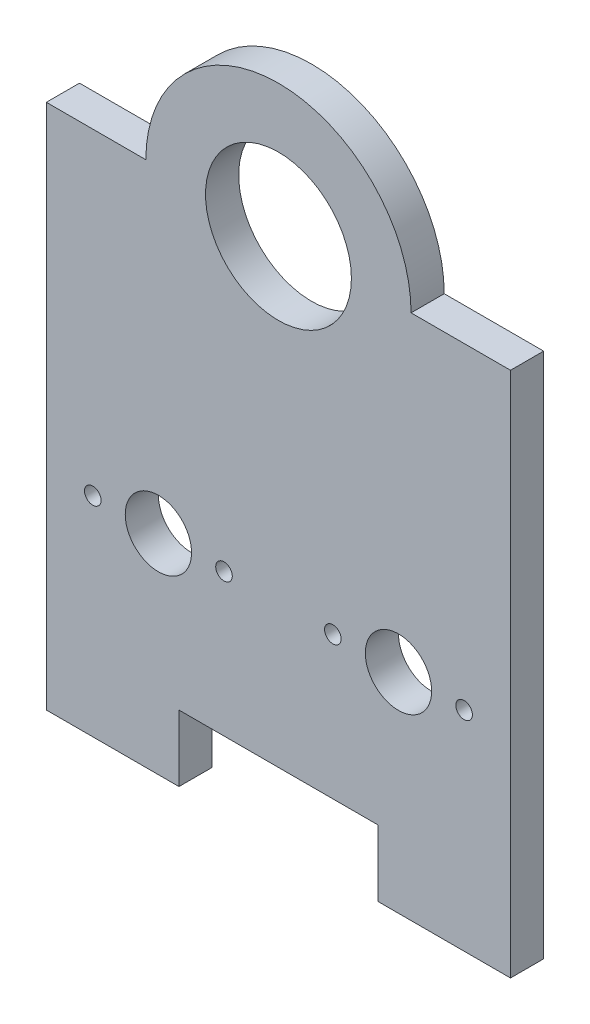
SolidWorks part; units mm, degrees
material "PPE"
ref_plane "Front Plane" through (0, 0, 0) normal (0, 0, 1) x (1, 0, 0)
ref_plane "Top Plane" through (0, 0, 0) normal (0, 1, 0) x (1, 0, 0)
ref_plane "Right Plane" through (0, 0, 0) normal (1, 0, 0) x (0, 0, -1)
sketch "Sketch1" plane through (0, 0, 0) normal (0, 0, 1) x (1, 0, 0)
  line L3 (-16.905, 47.8769) -> (-1.9, 47.8769)
  line L4 (-16.905, 47.8769) -> (-16.905, -21.5)
  line L6 (53.095, 47.8769) -> (53.095, -21.5)
  line L7 (38.1, 47.8769) -> (53.095, 47.8769)
  line L9 (3.095, -21.5) -> (33.095, -21.5)
  line L12 (-16.905, -21.5) -> (-16.905, -31.5)
  line L13 (-16.905, -31.5) -> (3.095, -31.5)
  line L14 (3.095, -21.5) -> (3.095, -31.5)
  line L15 (18.1, 47.8769) -> (18.095, -21.5) construction
  line L17 (53.095, -21.5) -> (53.095, -31.5)
  line L18 (53.095, -31.5) -> (33.095, -31.5)
  line L19 (33.095, -21.5) -> (33.095, -31.5)
  arc A9 (38.1, 47.8769) -> (-1.9, 47.8769) centre (18.1, 47.8769) ccw
  circle A10 centre (18.1, 47.8769) radius 11
  circle A11 centre (46.095, 0) radius 1.25
  circle A12 centre (36.2, 0) radius 5
  circle A13 centre (26.305, 0) radius 1.25
  circle A14 centre (-9.9019, 0.004) radius 1.25
  circle A15 centre (9.8881, 0.0012) radius 1.25
  circle A16 centre (-0.0069, 0.0026) radius 5
  point P15 (18.0952, 0.3415)
  dimension "D3" = 10
  dimension "D8" = 70
  dimension "D11" = 40
  dimension "D12" = 22
  dimension "D13" = 9.895
  dimension "D9" = 20
  dimension "D4" = 20
  dimension "D14" = 9.895
  dimension "D15" = 7
  dimension "D17" = 18.1
  dimension "D16" = 21.5
extrude "Boss-Extrude7" add sketch "Sketch1" along normal blind 5
